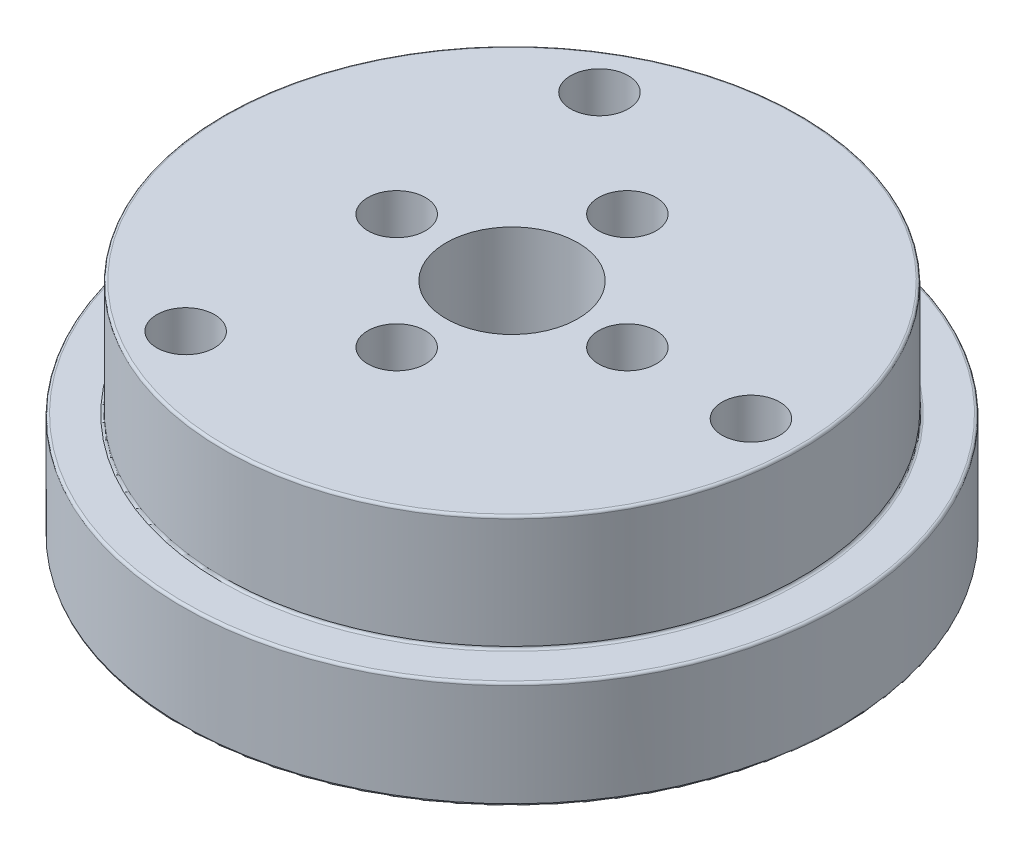
SolidWorks part; units mm, degrees
ref_plane "Front Plane" through (0, 0, 0) normal (0, 0, 1) x (1, 0, 0)
ref_plane "Top Plane" through (0, 0, 0) normal (0, 1, 0) x (1, 0, 0)
ref_plane "Right Plane" through (0, 0, 0) normal (1, 0, 0) x (0, 0, -1)
sketch "Sketch1" plane through (0, 0, 0) normal (0, 0, 1) x (1, 0, 0)
  line L0 (0, 0) -> (-20, 0)
  line L1 (-20, 0) -> (-20, 6.5)
  line L2 (-20, 6.5) -> (-17.5, 6.5)
  line L3 (-17.5, 6.5) -> (-17.5, 13.5)
  line L4 (-17.5, 13.5) -> (0, 13.5)
  line L5 (0, 13.5) -> (0, 0)
  dimension "D1" = 13.5
  dimension "D2" = 20
  dimension "D3" = 6.5
  dimension "D4" = 17.5
revolve "Revolve1" add sketch "Sketch1" angle 360 about L5
sketch "Sketch2" plane through (0, 0, 0) normal (0, -1, 0) x (1, 0, 0)
  line L0 (0, 7) -> (0, -7) construction
  line L1 (7, 0) -> (-7, 0) construction
  circle A0 centre (0, 0) radius 10
  circle A1 centre (14.5, 0) radius 1.75
  circle A2 centre (0, 0) radius 10
  circle A3 centre (-7.25, -12.5574) radius 1.75
  circle A4 centre (0, 0) radius 10
  circle A5 centre (-7.25, 12.5574) radius 1.75
  circle A7 centre (0, 0) radius 4
  circle A8 centre (7, 0) radius 1.75
  circle A11 centre (0, -7) radius 1.75
  circle A12 centre (-7, 0) radius 1.75
  circle A13 centre (0, 7) radius 1.75
  point P14 (0, 0)
  point P22 (0, 0)
  point P25 (0, 0)
  dimension "D1" = 20
  dimension "D2" = 3.5
  dimension "D5" = 8
  dimension "D6" = 3.5
  dimension "D9" = 14
  dimension "D3" = 14.5
  dimension "D7" = 14
  dimension "D4" = 3
  dimension "D8" = 4
extrude "Cut-Extrude4" cut sketch "Sketch2" against normal through all contours A5 | A3 | A1 | A8 | A11 | A12 | A13 | A7
sketch "Sketch7" plane through (0, 0, 0) normal (0, -1, 0) x (1, 0, 0)
  circle A0 centre (0, 0) radius 11
  dimension "D1" = 22
extrude "Cut-Extrude5" cut sketch "Sketch7" against normal blind 7.5
fillet "Fillet1" radius 0.15 4 edges at (-20, 0, 0) (-17.5, 13.5, 0) (-17.5, 6.5, 0) (-20, 6.5, 0)
